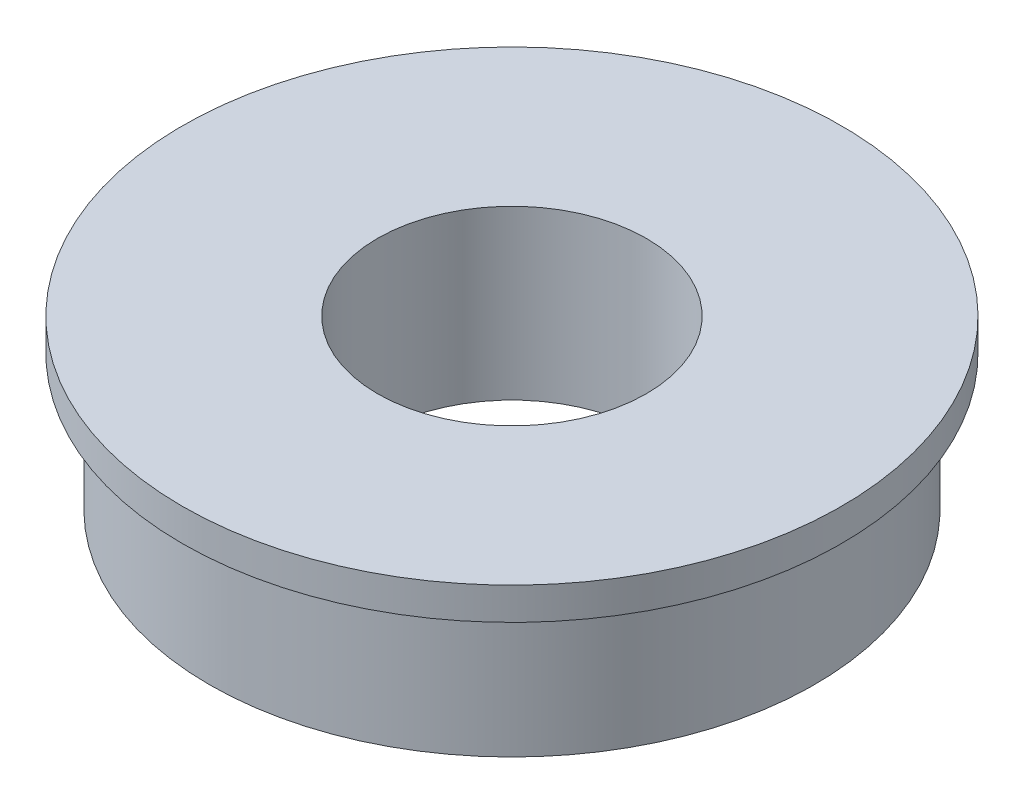
SolidWorks part; units mm, degrees
material "Cast Stainless Steel"
ref_plane "Front Plane" through (0, 0, 0) normal (0, 0, 1) x (1, 0, 0)
ref_plane "Top Plane" through (0, 0, 0) normal (0, 1, 0) x (1, 0, 0)
ref_plane "Right Plane" through (0, 0, 0) normal (1, 0, 0) x (0, 0, -1)
sketch "Sketch1" plane through (0, 0, 0) normal (0, 1, 0) x (1, 0, 0)
  circle A0 centre (0, 0) radius 14.2875
  dimension "D1" = 28.575
extrude "Boss-Extrude1" add sketch "Sketch1" along normal blind 7.9248
sketch "Sketch2" plane through (0, 7.9248, 0) normal (0, 1, 0) x (1, 0, 0)
  circle A0 centre (0, 0) radius 15.5575
  dimension "D1" = 31.115
extrude "Boss-Extrude2" add sketch "Sketch2" against normal blind 1.524
sketch "Sketch3" plane through (0, 7.9248, 0) normal (0, 1, 0) x (1, 0, 0)
  circle A0 centre (0, 0) radius 6.35
  dimension "D1" = 12.7
extrude "Cut-Extrude1" cut sketch "Sketch3" against normal through all
